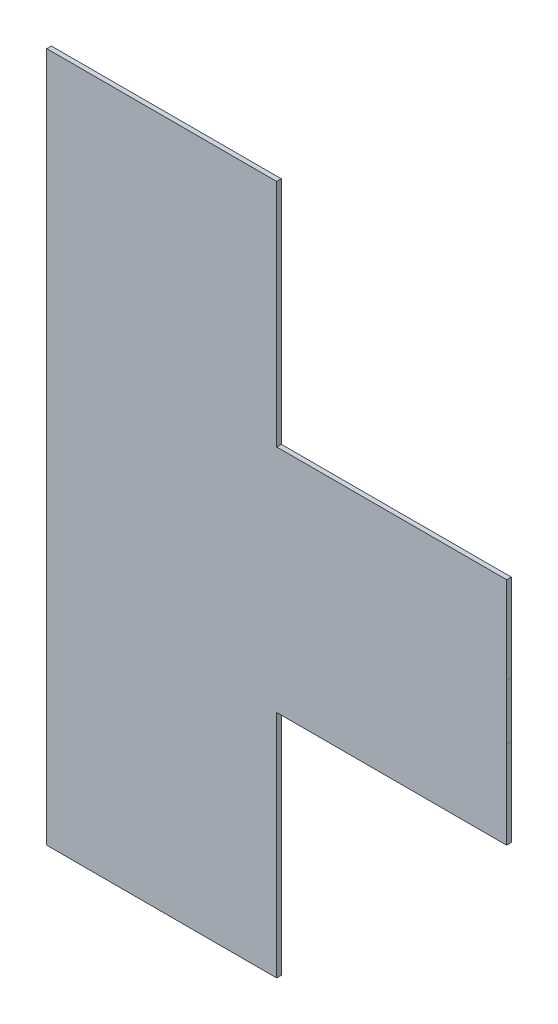
SolidWorks part; units mm, degrees
ref_plane "Front Plane" through (0, 0, 0) normal (0, 0, 1) x (1, 0, 0)
ref_plane "Top Plane" through (0, 0, 0) normal (0, 1, 0) x (1, 0, 0)
ref_plane "Right Plane" through (0, 0, 0) normal (1, 0, 0) x (0, 0, -1)
sketch "Sketch1" plane through (0, 0, 0) normal (0, 0, 1) x (1, 0, 0)
  line L12 (50, 100) -> (50, 150)
  line L13 (0, 0) -> (50, 0)
  line L14 (0, 0) -> (0, 150)
  line L15 (0, 150) -> (50, 150)
  line L16 (50, 0) -> (50, 50)
  line L17 (50, 100) -> (100, 100)
  line L19 (50, 50) -> (100, 50)
  line L20 (100, 100) -> (100, 50)
  dimension "D1" = 50
  dimension "D2" = 50
  dimension "D3" = 50
  dimension "D4" = 50
  dimension "D5" = 50
extrude "Boss-Extrude1" add sketch "Sketch1" along normal blind 1
ref_plane "Plane1" through (100, 0, 0) normal (1, 0, 0) x (0, 0, -1)
sketch "Sketch2" plane through (100, 0, 0) normal (1, 0, 0) x (0, 0, -1)
  line L0 (-1, 100) -> (-1, 50) construction
  line L1 (-1, 81) -> (0, 81)
  line L2 (-1, 81) -> (-1, 69)
  line L3 (-1, 69) -> (0, 69)
  line L4 (0, 81) -> (0, 69)
  line L5 (0, 100) -> (0, 50) construction
  line L6 (-1, 100) -> (0, 100) construction
  dimension "D1" = 12
  dimension "D2" = 19
split line "Split Line1"
